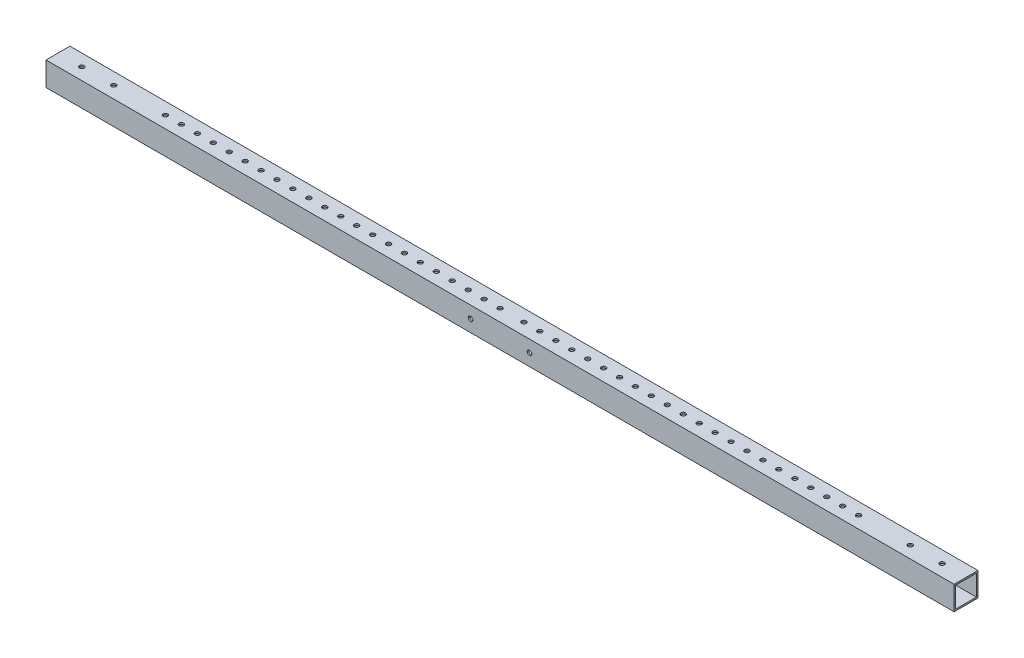
SolidWorks part; units mm, degrees
material "Thornel Mat VMA"
ref_plane "前视基准面" through (0, 0, 0) normal (0, 0, 1) x (1, 0, 0)
ref_plane "上视基准面" through (0, 0, 0) normal (0, 1, 0) x (1, 0, 0)
ref_plane "右视基准面" through (0, 0, 0) normal (1, 0, 0) x (0, 0, -1)
other "Configuration Table"
sketch "草图1" plane through (0, 0, 0) normal (0, 1, 0) x (1, 0, 0)
  line L0 (-285, 0) -> (285, 0)
  dimension "D1" = 570
other "铝管 15X15X1(1)"
ref_plane "基准面1" through (-285, 0, 0) normal (1, 0, 0) x (0, 0, -1)
sketch "草图11" plane through (-285, 0, 0) normal (1, 0, 0) x (0, 0, -1)
  line L1 (-7.5, -7.5) -> (7.5, -7.5)
  line L2 (-7.5, -7.5) -> (-7.5, 7.5)
  line L3 (-7.5, 7.5) -> (7.5, 7.5)
  line L4 (7.5, -7.5) -> (7.5, 7.5)
  line L5 (-7.5, -7.5) -> (7.5, 7.5) construction
  line L6 (-7.5, 7.5) -> (7.5, -7.5) construction
  line L7 (-6.5, -6.5) -> (6.5, -6.5)
  line L8 (-6.5, -6.5) -> (-6.5, 6.5)
  line L9 (-6.5, 6.5) -> (6.5, 6.5)
  line L10 (6.5, -6.5) -> (6.5, 6.5)
  line L11 (-6.5, -6.5) -> (6.5, 6.5) construction
  line L12 (-6.5, 6.5) -> (6.5, -6.5) construction
  point P0 (0, 0)
  point P6 (0, 0)
  point P11 (0, 0)
  dimension "D1" = 15
  dimension "D2" = 15
  dimension "D3" = 13
  dimension "D4" = 13
sketch "草图12" plane through (0, 7.5, 0) normal (0, 1, 0) x (1, 0, 0)
  line L0 (-285, 0) -> (285, 0) construction
  line L1 (-285, 7.5) -> (-285, -7.5) construction
  line L2 (0, 7.5) -> (0, -7.5) construction
  line L3 (285, 7.5) -> (-285, 7.5) construction
  line L4 (285, -7.5) -> (-285, -7.5) construction
  circle A0 centre (-270, 0) radius 1.45
  circle A1 centre (-250, 0) radius 1.45
  circle A2 centre (250, 0) radius 1.45
  circle A3 centre (270, 0) radius 1.45
  dimension "D1" = 2.9
  dimension "D3" = 2.9
  dimension "D4" = 20
  dimension "D2" = 15
extrude "切除-拉伸1" cut sketch "草图12" against normal through all
sketch "草图13" plane through (0, 0, -7.5) normal (0, 0, -1) x (-1, 0, 0)
  line L0 (0, 7.5) -> (0, -7.5) construction
  line L1 (-285, 7.5) -> (285, 7.5) construction
  line L2 (-285, -7.5) -> (285, -7.5) construction
  line L3 (285, 0) -> (-285, 0) construction
  circle A0 centre (-18.5, 0) radius 1.45
  circle A1 centre (18.5, 0) radius 1.45
  dimension "D1" = 2.9
  dimension "D2" = 2.9
  dimension "D3" = 18.5
  dimension "D4" = 18.5
extrude "切除-拉伸2" cut sketch "草图13" against normal through all
sketch "草图14" plane through (0, -7.5, 0) normal (0, -1, 0) x (1, 0, 0)
  line L0 (-92.5, 7.5) -> (-92.5, -7.5) construction
  line L1 (285, 7.5) -> (-285, 7.5) construction
  line L2 (285, -7.5) -> (-285, -7.5) construction
  line L3 (0, 7.5) -> (0, -7.5) construction
  line L4 (-285, 0) -> (285, 0) construction
  line L5 (12.5, 7.5) -> (12.5, -7.5) construction
  line L6 (-112.5, 7.5) -> (-112.5, -7.5) construction
  line L7 (-132.5, 7.5) -> (-132.5, -7.5) construction
  line L8 (-152.5, 7.5) -> (-152.5, -7.5) construction
  line L9 (-172.5, 7.5) -> (-172.5, -7.5) construction
  line L10 (-192.5, 7.5) -> (-192.5, -7.5) construction
  line L11 (-212.5, 7.5) -> (-212.5, -7.5) construction
  line L12 (32.5, 7.5) -> (32.5, -7.5) construction
  line L13 (52.5, 7.5) -> (52.5, -7.5) construction
  line L14 (72.5, 7.5) -> (72.5, -7.5) construction
  line L15 (212.5, 7.5) -> (212.5, -7.5) construction
  line L16 (192.5, 7.5) -> (192.5, -7.5) construction
  line L17 (172.5, 7.5) -> (172.5, -7.5) construction
  line L18 (-72.5, 7.5) -> (-72.5, -7.5) construction
  line L19 (-52.5, 7.5) -> (-52.5, -7.5) construction
  line L20 (-32.5, 7.5) -> (-32.5, -7.5) construction
  line L21 (-12.5, 7.5) -> (-12.5, -7.5) construction
  line L22 (152.5, 7.5) -> (152.5, -7.5) construction
  line L23 (132.5, 7.5) -> (132.5, -7.5) construction
  line L24 (112.5, 7.5) -> (112.5, -7.5) construction
  line L25 (92.5, 7.5) -> (92.5, -7.5) construction
  circle A0 centre (-97.5, 0) radius 1.45
  circle A1 centre (-87.5, 0) radius 1.45
  circle A4 centre (-117.5, 0) radius 1.45
  circle A5 centre (-107.5, 0) radius 1.45
  circle A6 centre (-137.5, 0) radius 1.45
  circle A7 centre (-127.5, 0) radius 1.45
  circle A8 centre (-157.5, 0) radius 1.45
  circle A9 centre (-147.5, 0) radius 1.45
  circle A10 centre (-177.5, 0) radius 1.45
  circle A11 centre (-167.5, 0) radius 1.45
  circle A12 centre (-197.5, 0) radius 1.45
  circle A13 centre (-187.5, 0) radius 1.45
  circle A14 centre (-217.5, 0) radius 1.45
  circle A15 centre (-207.5, 0) radius 1.45
  circle A28 centre (-77.5, 0) radius 1.45
  circle A29 centre (-67.5, 0) radius 1.45
  circle A30 centre (-57.5, 0) radius 1.45
  circle A31 centre (-47.5, 0) radius 1.45
  circle A32 centre (-37.5, 0) radius 1.45
  circle A33 centre (-27.5, 0) radius 1.45
  circle A34 centre (-17.5, 0) radius 1.45
  circle A35 centre (-7.5, 0) radius 1.45
  circle A45 centre (7.5, 0) radius 1.45
  circle A46 centre (17.5, 0) radius 1.45
  circle A47 centre (27.5, 0) radius 1.45
  circle A48 centre (37.5, 0) radius 1.45
  circle A49 centre (47.5, 0) radius 1.45
  circle A50 centre (57.5, 0) radius 1.45
  circle A51 centre (67.5, 0) radius 1.45
  circle A52 centre (77.5, 0) radius 1.45
  circle A53 centre (207.5, 0) radius 1.45
  circle A54 centre (217.5, 0) radius 1.45
  circle A55 centre (187.5, 0) radius 1.45
  circle A56 centre (197.5, 0) radius 1.45
  circle A57 centre (167.5, 0) radius 1.45
  circle A58 centre (177.5, 0) radius 1.45
  circle A59 centre (147.5, 0) radius 1.45
  circle A60 centre (157.5, 0) radius 1.45
  circle A61 centre (127.5, 0) radius 1.45
  circle A62 centre (137.5, 0) radius 1.45
  circle A63 centre (107.5, 0) radius 1.45
  circle A64 centre (117.5, 0) radius 1.45
  circle A65 centre (87.5, 0) radius 1.45
  circle A66 centre (97.5, 0) radius 1.45
  dimension "D2" = 2.9
  dimension "D3" = 2.9
  dimension "D1" = 92.5
  dimension "D4" = 5
  dimension "D5" = 5
  dimension "D7" = 20
  dimension "D9" = 20
  dimension "D6" = 7
  dimension "D8" = 5
extrude "切除-拉伸3" cut sketch "草图14" against normal through all
sketch "草图15" plane through (0, -7.5, 0) normal (0, -1, 0) x (1, 0, 0)
  line L1 (-85, -7.5) -> (85, -7.5)
  line L2 (-85, -7.5) -> (-85, 7.5)
  line L3 (-85, 7.5) -> (85, 7.5)
  line L4 (85, -7.5) -> (85, 7.5)
  line L5 (-85, -7.5) -> (85, 7.5) construction
  line L6 (-85, 7.5) -> (85, -7.5) construction
  point P0 (0, 0)
  dimension "D1" = 15
  dimension "D2" = 170
extrude "切除-拉伸4" [suppressed] cut sketch "草图15" against normal through all
